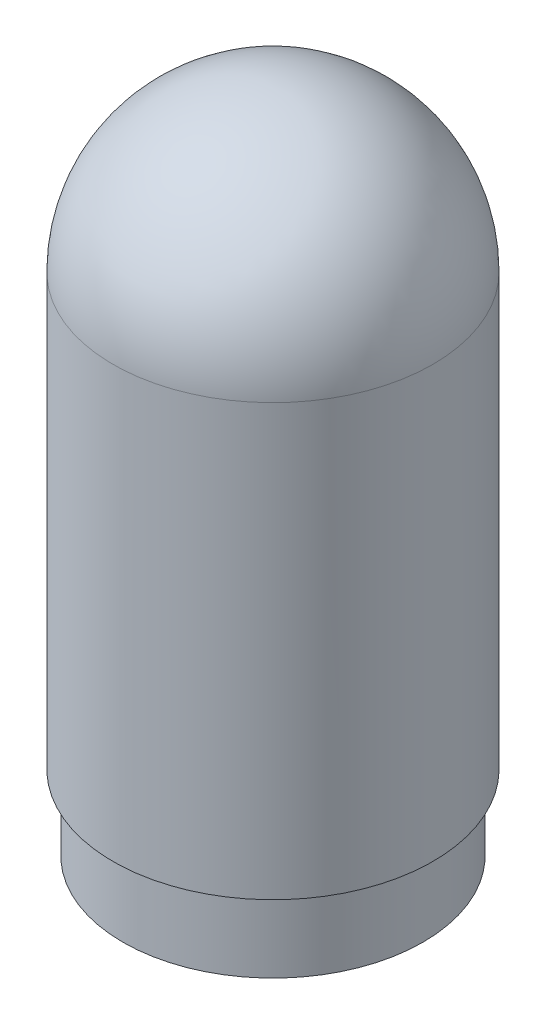
SolidWorks part; units mm, degrees
ref_plane "Front Plane" through (0, 0, 0) normal (0, 0, 1) x (1, 0, 0)
ref_plane "Top Plane" through (0, 0, 0) normal (0, 1, 0) x (1, 0, 0)
ref_plane "Right Plane" through (0, 0, 0) normal (1, 0, 0) x (0, 0, -1)
sketch "Sketch1" plane through (0, 0, 0) normal (0, 1, 0) x (1, 0, 0)
  circle A0 centre (0, 0) radius 30.5
  circle A1 centre (0, 0) radius 22.5
extrude "Boss-Extrude2" add sketch "Sketch1" along normal blind 15
sketch "Sketch5" plane through (0, 0, 0) normal (0, 0, 1) x (1, 0, 0)
  line L0 (0, 24.3003) -> (0, 49.0135) construction
  line L1 (0, 15.2089) -> (32.5, 15.2089)
  line L2 (32.5, 15.2089) -> (32.5, 102.7089)
  line L3 (0, 15.2089) -> (0, 135.2089)
  arc A0 (0, 135.2089) -> (32.5, 102.7089) centre (0, 102.7089) cw
  dimension "D1" = 32.5
  dimension "D2" = 120
revolve "Revolve2" add sketch "Sketch5" angle 360 about L0
sketch "Sketch6" plane through (0, 0, 0) normal (0, 0, 1) x (1, 0, 0)
  line L0 (0, 102.7089) -> (0, 79.8784) construction
  line L1 (22.5, 15) -> (22.5, 102.7089)
  line L2 (22.5, 15) -> (0, 15)
  line L3 (30.5, 15) -> (-30.5, 15) construction
  line L4 (32.5, 102.7089) -> (-32.5, 102.7089) construction
  line L5 (0, 125.2089) -> (0, 15)
  arc A0 (22.5, 102.7089) -> (0, 125.2089) centre (0, 102.7089) ccw
revolve "Cut-Revolve2" cut sketch "Sketch6" angle 360 about L0
